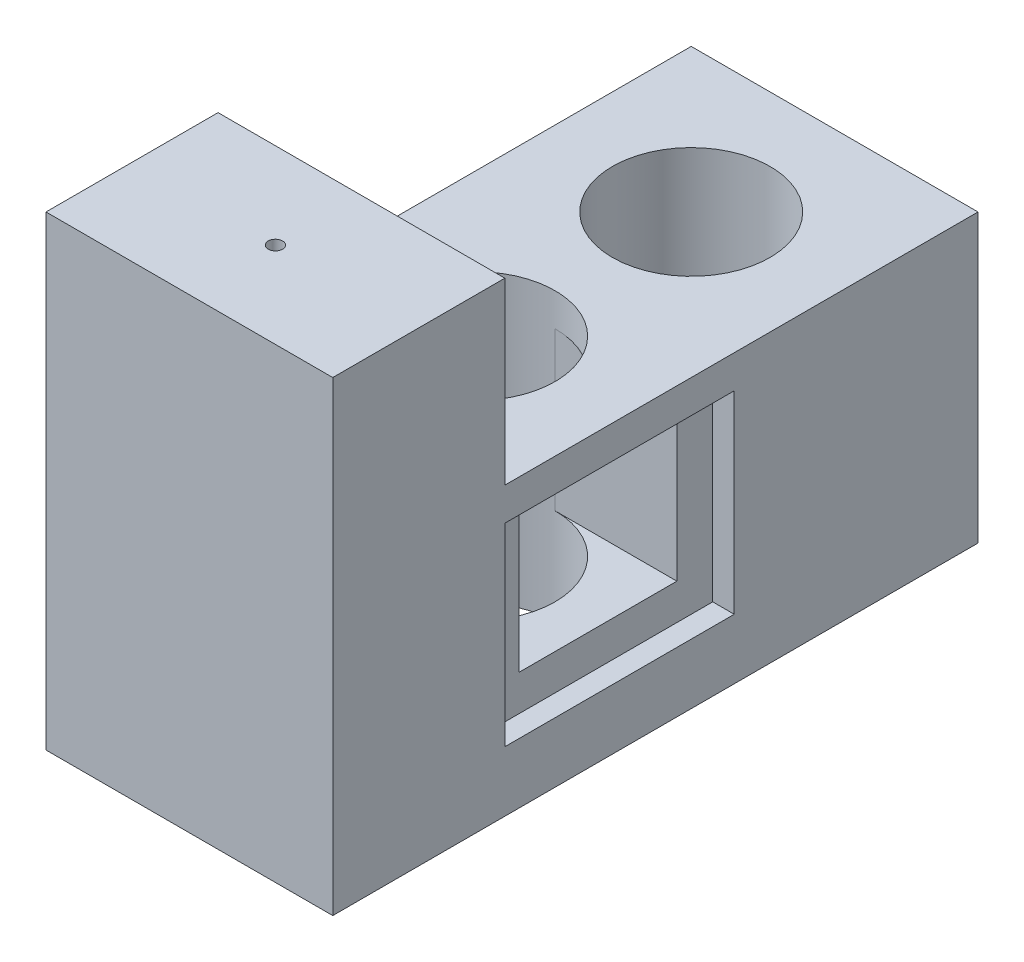
SolidWorks part; units mm, degrees
ref_plane "Alzado" through (0, 0, 0) normal (0, 0, 1) x (1, 0, 0)
ref_plane "Planta" through (0, 0, 0) normal (0, 1, 0) x (1, 0, 0)
ref_plane "Vista lateral" through (0, 0, 0) normal (1, 0, 0) x (0, 0, -1)
sketch "Croquis1" plane through (0, 0, 0) normal (0, 1, 0) x (1, 0, 0)
  line L0 (-428.2265, 18.5302) -> (-428.2265, 43.5648) construction
  line L1 (-418.2265, 43.5302) -> (-438.2265, 43.5302)
  line L2 (-418.2265, 43.5302) -> (-418.2265, 8.5302)
  line L3 (-418.2265, 8.5302) -> (-438.2265, 8.5302)
  line L4 (-438.2265, 43.5302) -> (-438.2265, 8.5302)
  line L5 (-418.2265, 43.5302) -> (-438.2265, 8.5302) construction
  line L6 (-418.2265, 8.5302) -> (-438.2265, 43.5302) construction
  circle A1 centre (-428.2265, 18.5302) radius 5
  circle A2 centre (-428.2265, 33.5302) radius 5
  dimension "D3" = 10
  dimension "D5" = 15
  dimension "D1" = 20
  dimension "D2" = 10
  dimension "D4" = 10
extrude "Saliente-Extruir1" add sketch "Croquis1" along normal blind 20
sketch "Croquis2" plane through (-418.2265, 0, 0) normal (1, 0, 0) x (0, 0, -1)
  line L1 (43.5302, 0) -> (-88, 0) construction
  line L2 (43.5302, 0) -> (43.5302, 20) construction
  line L3 (43.5302, 20) -> (8.5302, 20) construction
  circle A0 centre (18.5302, 12.2) radius 2
  point P0 (18.5302, 12.2)
  dimension "D1" = 25
  dimension "D2" = 12.2
extrude "Saliente-Extruir2" add sketch "Croquis2" along normal blind 8
sketch "Croquis3" plane through (0, 0, -8.5302) normal (0, 0, 1) x (1, 0, 0)
  line L1 (-438.2265, 20) -> (-418.2265, 20)
  line L2 (-438.2265, 20) -> (-438.2265, 0)
  line L3 (-438.2265, 0) -> (-418.2265, 0)
  line L4 (-418.2265, 20) -> (-418.2265, 0)
extrude "Saliente-Extruir3" add sketch "Croquis3" along normal blind 10
sketch "Croquis4" plane through (0, 20, 0) normal (0, 1, 0) x (1, 0, 0)
  line L0 (-428.2265, 33.5302) -> (-428.2265, 18.5302) construction
  line L3 (-418.2265, -1.4698) -> (-438.2265, -1.4698) construction
  line L5 (-428.2265, 33.5302) -> (-428.2265, -4.9348) construction
  circle A0 centre (-428.2265, 18.5302) radius 5 construction
  circle A1 centre (-428.2265, 33.5302) radius 5 construction
  circle A2 centre (-428.2265, 4.5302) radius 0.5
  dimension "D1" = 1
  dimension "D2" = 6
extrude "Cortar-Extruir1" cut sketch "Croquis4" against normal up to next
sketch "Croquis5" plane through (0, 20, 0) normal (0, 1, 0) x (1, 0, 0)
  line L0 (-438.2265, 43.5302) -> (-438.2265, -1.4698) construction
  line L1 (-418.2265, -1.4698) -> (-438.2265, -1.4698)
  line L2 (-418.2265, -1.4698) -> (-418.2265, 10.5302)
  line L3 (-418.2265, 10.5302) -> (-438.2265, 10.5302)
  line L4 (-438.2265, -1.4698) -> (-438.2265, 10.5302)
  circle A0 centre (-428.2265, 4.5302) radius 0.5
  circle A1 centre (-428.2265, 4.5302) radius 0.5 construction
  dimension "D1" = 12
extrude "Saliente-Extruir4" add sketch "Croquis5" along normal blind 12.5
sketch "Croquis6" plane through (0, 20, 0) normal (0, 1, 0) x (1, 0, 0)
  circle A0 centre (-428.2265, 18.5302) radius 5.5
  circle A1 centre (-428.2265, 33.5302) radius 5.5
extrude "Cortar-Extruir2" cut sketch "Croquis6" against normal through all
sketch "Croquis7" plane through (-410.2265, 0, 0) normal (1, 0, 0) x (0, 0, -1)
  line L1 (24.0302, 17.7) -> (13.0302, 17.7)
  line L2 (24.0302, 17.7) -> (24.0302, 6.7)
  line L3 (24.0302, 6.7) -> (13.0302, 6.7)
  line L4 (13.0302, 17.7) -> (13.0302, 6.7)
  line L5 (24.0302, 17.7) -> (13.0302, 6.7) construction
  line L6 (24.0302, 6.7) -> (13.0302, 17.7) construction
  point P0 (18.5302, 12.2)
  dimension "D1" = 11
  dimension "D2" = 11
extrude "Cortar-Extruir3" cut sketch "Croquis7" against normal blind 18
sketch "Croquis8" plane through (-418.2265, 0, 0) normal (1, 0, 0) x (0, 0, -1)
  line L0 (13.0302, 17.7) -> (24.0302, 17.7) construction
  line L1 (10.5302, 17.7) -> (26.5302, 17.7)
  line L2 (10.5302, 17.7) -> (10.5302, 4.2)
  line L3 (10.5302, 4.2) -> (26.5302, 4.2)
  line L4 (26.5302, 17.7) -> (26.5302, 4.2)
  line L5 (24.0302, 17.7) -> (24.0302, 6.7) construction
  line L6 (13.0302, 6.7) -> (13.0302, 17.7) construction
  line L7 (24.0302, 6.7) -> (13.0302, 6.7) construction
  dimension "D1" = 2.5
  dimension "D2" = 2.5
  dimension "D3" = 2.5
extrude "Cortar-Extruir4" cut sketch "Croquis8" against normal blind 1.5
